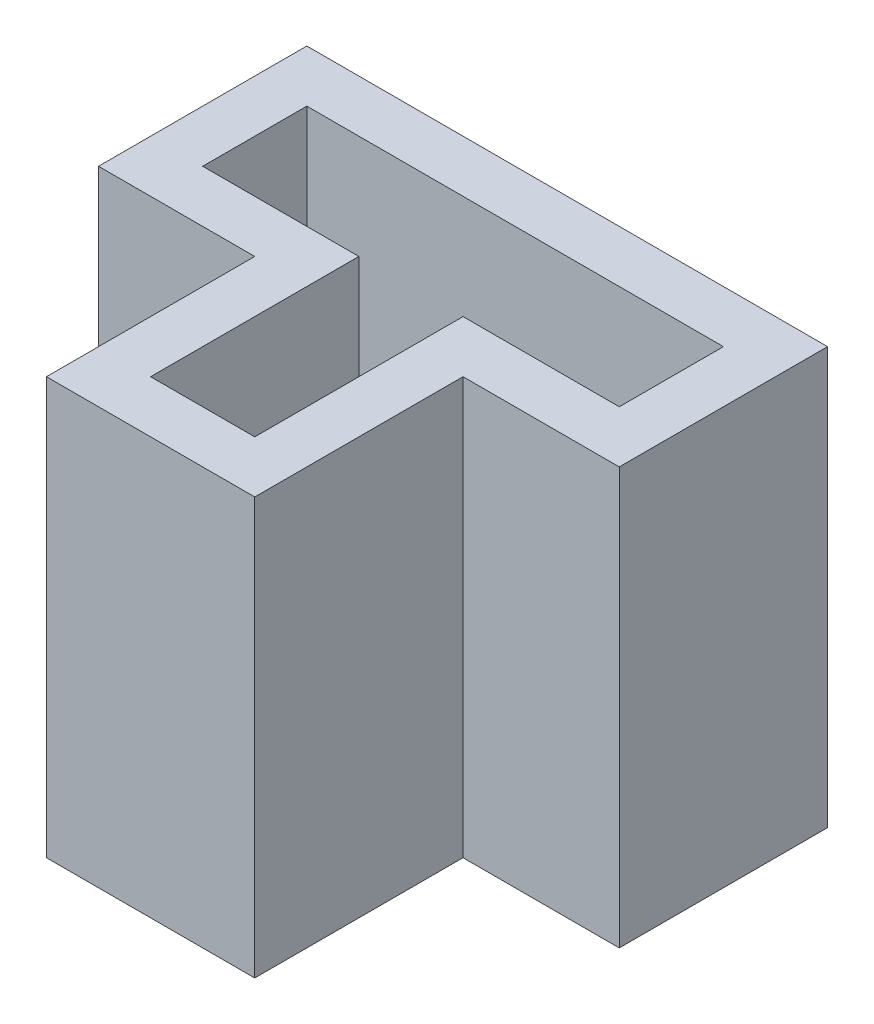
SolidWorks part; units mm, degrees
ref_plane "Front Plane" through (0, 0, 0) normal (0, 0, 1) x (1, 0, 0)
ref_plane "Top Plane" through (0, 0, 0) normal (0, 1, 0) x (1, 0, 0)
ref_plane "Right Plane" through (0, 0, 0) normal (1, 0, 0) x (0, 0, -1)
sketch "Sketch1" plane through (0, 0, 0) normal (0, 1, 0) x (1, 0, 0)
  line L0 (32.9487, 4.188) -> (-17.0513, 4.188)
  line L1 (-17.0513, 4.188) -> (-17.0513, -15.812)
  line L2 (-17.0513, -15.812) -> (-2.0513, -15.812)
  line L3 (-2.0513, -15.812) -> (-2.0513, -35.812)
  line L4 (-2.0513, -35.812) -> (17.9487, -35.812)
  line L5 (17.9487, -35.812) -> (17.9487, -15.812)
  line L6 (17.9487, -15.812) -> (32.9487, -15.812)
  line L7 (32.9487, -15.812) -> (32.9487, 4.188)
  dimension "D1" = 20
  dimension "D2" = 15
  dimension "D3" = 15
  dimension "D4" = 20
  dimension "D5" = 20
  dimension "D6" = 20
sketch "Sketch3" plane through (0, 0, 0) normal (0, 1, 0) x (1, 0, 0)
  line L8 (27.9487, -0.812) -> (-12.0513, -0.812)
  line L9 (-12.0513, -0.812) -> (-12.0513, -10.812)
  line L10 (-12.0513, -10.812) -> (2.9487, -10.812)
  line L11 (2.9487, -10.812) -> (2.9487, -30.812)
  line L12 (2.9487, -30.812) -> (12.9487, -30.812)
  line L13 (12.9487, -30.812) -> (12.9487, -10.812)
  line L14 (12.9487, -10.812) -> (27.9487, -10.812)
  line L15 (27.9487, -10.812) -> (27.9487, -0.812)
  line L16 (-12.0513, -0.812) -> (-12.0513, -10.812)
  line L17 (27.9487, -0.812) -> (-12.0513, -0.812)
  line L18 (27.9487, -10.812) -> (27.9487, -0.812)
  line L19 (12.9487, -10.812) -> (27.9487, -10.812)
  line L20 (12.9487, -30.812) -> (12.9487, -10.812)
  line L21 (2.9487, -30.812) -> (12.9487, -30.812)
  line L22 (2.9487, -10.812) -> (2.9487, -30.812)
  line L23 (-12.0513, -10.812) -> (2.9487, -10.812)
  line L24 (-12.0513, -0.812) -> (-12.0513, -10.812) construction
  line L25 (27.9487, -0.812) -> (-12.0513, -0.812) construction
  line L26 (27.9487, -10.812) -> (27.9487, -0.812) construction
  line L27 (12.9487, -10.812) -> (27.9487, -10.812) construction
  line L28 (12.9487, -30.812) -> (12.9487, -10.812) construction
  line L29 (2.9487, -30.812) -> (12.9487, -30.812) construction
  line L30 (2.9487, -10.812) -> (2.9487, -30.812) construction
  line L31 (-12.0513, -10.812) -> (2.9487, -10.812) construction
  dimension "D1" = 5
extrude "Boss-Extrude2" add sketch "Sketch1" against normal blind 40
extrude "Cut-Extrude1" cut sketch "Sketch3" against normal blind 40
